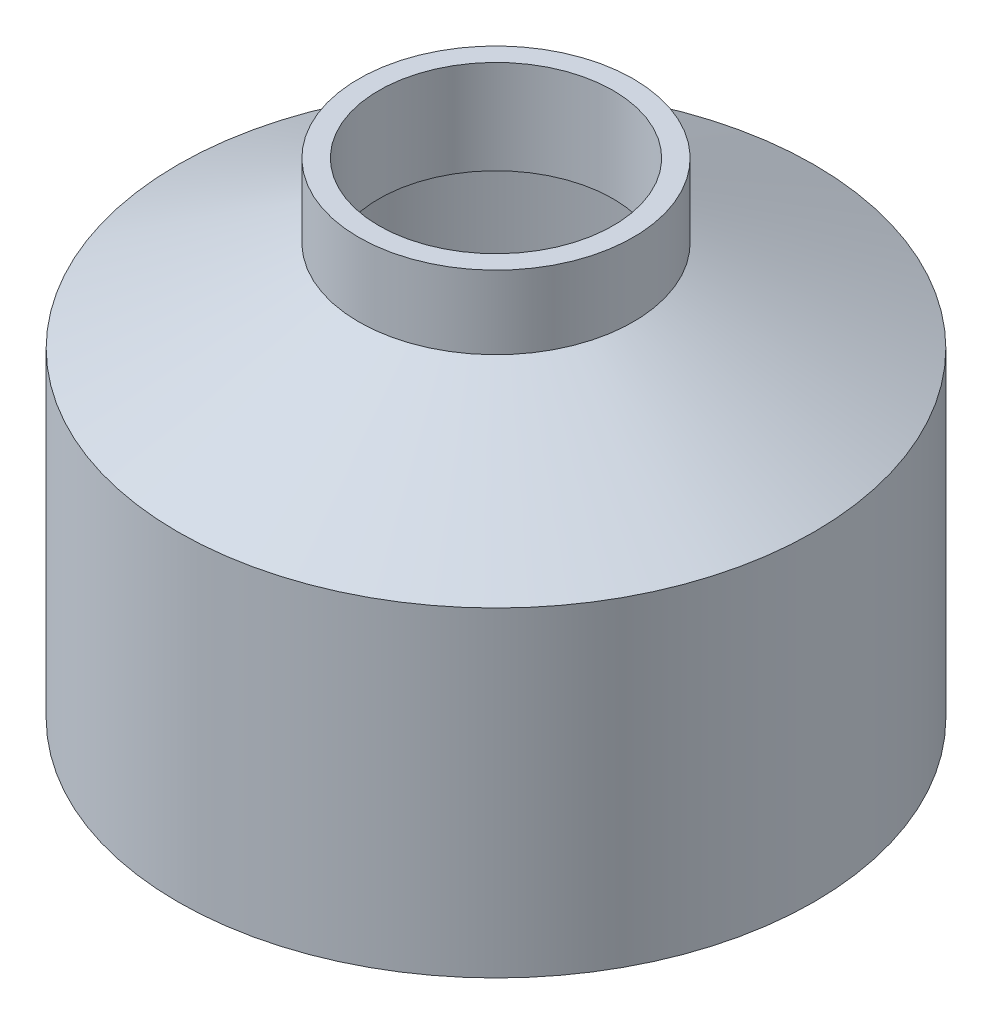
SolidWorks part; units mm, degrees
ref_plane "정면" through (0, 0, 0) normal (0, 0, 1) x (1, 0, 0)
ref_plane "윗면" through (0, 0, 0) normal (0, 1, 0) x (1, 0, 0)
ref_plane "우측면" through (0, 0, 0) normal (1, 0, 0) x (0, 0, -1)
sketch "스케치1" plane through (0, 0, 0) normal (0, 1, 0) x (1, 0, 0)
  circle A0 centre (0, 0) radius 34.75
  dimension "D1" = 69.5
extrude "보스-돌출1" add sketch "스케치1" along normal blind 35
ref_plane "평면1" through (0, 45, 0) normal (0, 1, 0) x (1, 0, 0)
sketch "스케치2" plane through (0, 45, 0) normal (0, 1, 0) x (1, 0, 0)
  circle A0 centre (0, 0) radius 15
  dimension "D1" = 30
extrude "보스-돌출2" add sketch "스케치2" along normal blind 8 separate body
loft "로프트1" add section face at (0, 35, 34.75) section face at (0, 45, 15)
shell "쉘2" thickness 3
sketch "스케치3" plane through (0, 53, 0) normal (0, 1, 0) x (1, 0, 0)
  circle A0 centre (0, 0) radius 12.8
  circle A1 centre (0, 0) radius 15 construction
  circle A2 centre (0, 0) radius 15
  dimension "D1" = 2.2
extrude "컷-돌출1" cut sketch "스케치3" against normal through all both and the other way through all contours A0
